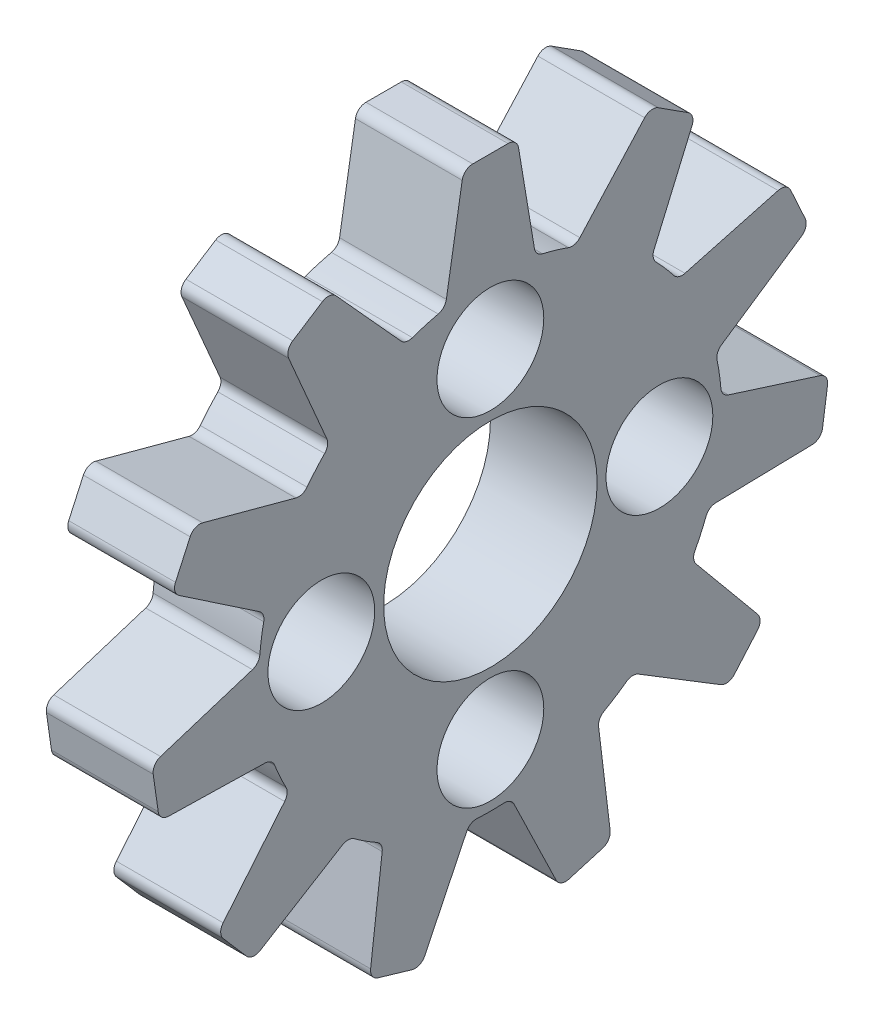
SolidWorks part; units mm, degrees
ref_plane "Front Plane" through (0, 0, 0) normal (0, 0, 1) x (1, 0, 0)
ref_plane "Top Plane" through (0, 0, 0) normal (0, 1, 0) x (1, 0, 0)
ref_plane "Right Plane" through (0, 0, 0) normal (1, 0, 0) x (0, 0, -1)
sketch "Sketch9" plane through (0, 0, 0) normal (1, 0, 0) x (0, 0, -1)
  circle A0 centre (0, 0) radius 6.5
  dimension "D1" = 13
extrude "Boss-Extrude3" add sketch "Sketch9" along normal blind 3
sketch "Sketch10" plane through (3, 0, 0) normal (1, 0, 0) x (0, 0, -1)
  line L0 (0, 6.5) -> (0, 9.5) construction
  line L1 (0, 9.5) -> (0.75, 9.5)
  line L2 (0, 9.5) -> (-0.75, 9.5)
  line L3 (0, 6.5) -> (0, 5) construction
  line L4 (0, 5) -> (-1.5, 5)
  line L5 (0, 5) -> (1.5, 5)
  line L6 (-0.75, 9.5) -> (-1.5, 5)
  line L7 (0.75, 9.5) -> (1.5, 5)
  circle A0 centre (0, 0) radius 6.5 construction
  dimension "D1" = 3
  dimension "D2" = 0.75
  dimension "D3" = 0.75
  dimension "D4" = 1.5
  dimension "D5" = 1.5
  dimension "D6" = 1.5
extrude "Boss-Extrude4" add sketch "Sketch10" against normal blind 3
fillet "Fillet9" radius 0.3 1 edges at (1.5, 9.5, -0.75)
fillet "Fillet10" radius 0.3 1 edges at (1.5, 9.5, 0.75)
fillet "Fillet11" radius 0.3 1 edges at (1.5, 6.3745, -1.2709)
fillet "Fillet12" radius 0.3 1 edges at (1.5, 6.3745, 1.2709)
pattern_circular "CirPattern6" count 11 over 360 about axis through (0, 0, 0) along (1, 0, 0) of "Boss-Extrude4", "Fillet9", "Fillet10", "Fillet11", "Fillet12"
sketch "Sketch11" plane through (3, 0, 0) normal (1, 0, 0) x (0, 0, -1)
  circle A0 centre (0, 0) radius 4.75 construction
  circle A1 centre (0, 4.75) radius 1.5
  circle A2 centre (4.75, 0) radius 1.5
  circle A3 centre (-4.75, 0) radius 1.5
  circle A4 centre (0, -4.75) radius 1.5
  dimension "D1" = 9.5
  dimension "D2" = 3
  dimension "D3" = 3
  dimension "D4" = 3
  dimension "D5" = 3
extrude "Cut-Extrude1" cut sketch "Sketch11" against normal blind 3
sketch "Sketch12" plane through (3, 0, 0) normal (1, 0, 0) x (0, 0, -1)
  circle A0 centre (0, 0) radius 3
  dimension "D1" = 6
extrude "Cut-Extrude2" cut sketch "Sketch12" against normal blind 3
